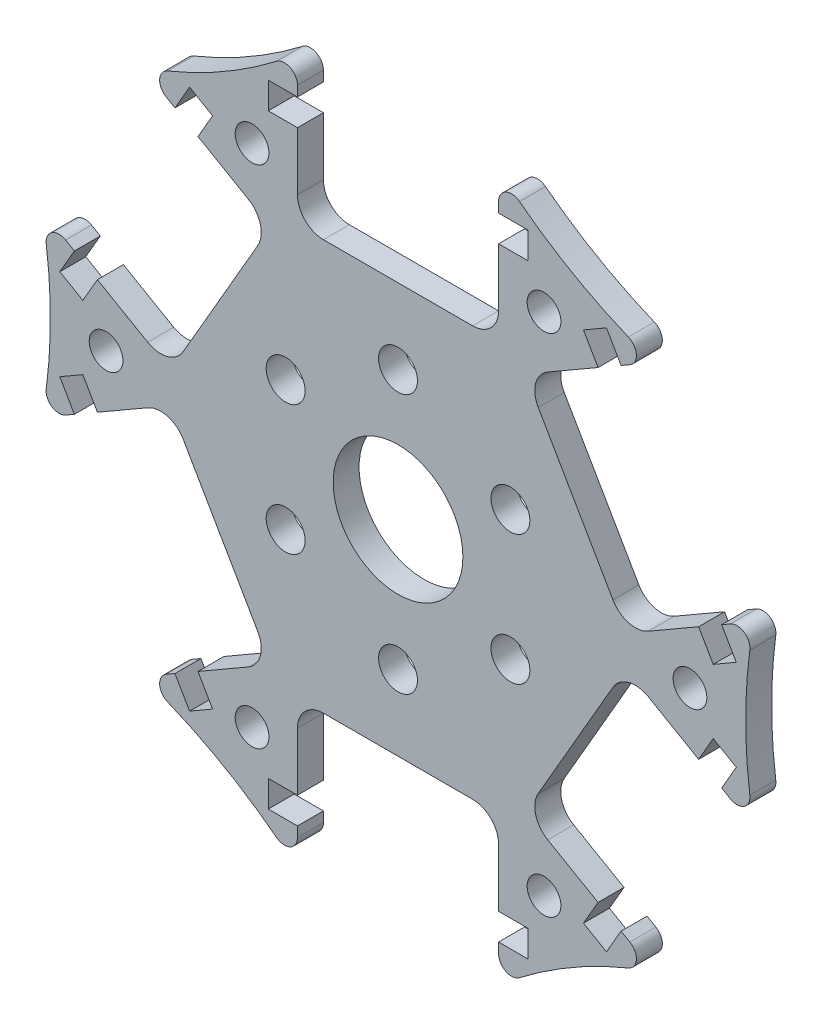
SolidWorks part; units mm, degrees
material "6061 合金"
ref_plane "Front" through (0, 0, 0) normal (0, 0, 1) x (1, 0, 0)
ref_plane "Top" through (0, 0, 0) normal (0, 1, 0) x (1, 0, 0)
ref_plane "Right" through (0, 0, 0) normal (1, 0, 0) x (0, 0, -1)
sketch "ｽｹｯﾁ1" plane through (0, 0, 0) normal (0, 0, 1) x (1, 0, 0)
  circle A0 centre (0, 0) radius 28.3
  dimension "D1" = 56.6
extrude "ﾎﾞｽ - 押し出し1" add sketch "ｽｹｯﾁ1" along normal blind 2
sketch "ｽｹｯﾁ2" plane through (0, 0, 2) normal (0, 0, 1) x (1, 0, 0)
  line L0 (0, 0) -> (0, 50000) construction
  line L1 (7.75, 24.325) -> (10, 24.325)
  line L2 (10, 24.325) -> (10, 22.275)
  line L3 (-7.75, 15.8) -> (-7.75, 22.275)
  line L4 (10, 22.275) -> (7.75, 22.275)
  line L5 (7.75, 27.2181) -> (7.75, 24.325)
  line L6 (7.75, 22.275) -> (7.75, 15.8)
  line L7 (7.75, 15.8) -> (-7.75, 15.8)
  line L8 (-7.75, 22.275) -> (-10, 22.275)
  line L9 (-10, 22.275) -> (-10, 24.325)
  line L10 (-10, 24.325) -> (-7.75, 24.325)
  line L11 (-7.75, 24.325) -> (-7.75, 27.2181)
  line L12 (0, 28.3) -> (16.8233, 28.3) construction
  line L13 (10, 23.3) -> (-10, 23.3) construction
  line L14 (0, 0) -> (28.3, 0) construction
  line L15 (24.9411, 5.4508) -> (26.0661, 3.5022)
  line L16 (26.0661, 3.5022) -> (24.2907, 2.4772)
  line L17 (9.8082, 14.6117) -> (15.4157, 17.8492)
  line L18 (24.2907, 2.4772) -> (23.1657, 4.4258)
  line L19 (27.4466, 6.8974) -> (24.9411, 5.4508)
  line L20 (23.1657, 4.4258) -> (17.5582, 1.1883)
  line L21 (17.5582, 1.1883) -> (9.8082, 14.6117)
  line L22 (15.4157, 17.8492) -> (14.2907, 19.7978)
  line L23 (14.2907, 19.7978) -> (16.0661, 20.8228)
  line L24 (16.0661, 20.8228) -> (17.1911, 18.8742)
  line L25 (17.1911, 18.8742) -> (19.6966, 20.3208)
  line L26 (25.1784, 2.9897) -> (15.1784, 20.3103) construction
  line L27 (17.1911, -18.8742) -> (16.0661, -20.8228)
  line L28 (16.0661, -20.8228) -> (14.2907, -19.7978)
  line L29 (17.5582, -1.1883) -> (23.1657, -4.4258)
  line L30 (14.2907, -19.7978) -> (15.4157, -17.8492)
  line L31 (19.6966, -20.3208) -> (17.1911, -18.8742)
  line L32 (15.4157, -17.8492) -> (9.8082, -14.6117)
  line L33 (9.8082, -14.6117) -> (17.5582, -1.1883)
  line L34 (23.1657, -4.4258) -> (24.2907, -2.4772)
  line L35 (24.2907, -2.4772) -> (26.0661, -3.5022)
  line L36 (26.0661, -3.5022) -> (24.9411, -5.4508)
  line L37 (24.9411, -5.4508) -> (27.4466, -6.8974)
  line L38 (15.1784, -20.3103) -> (25.1784, -2.9897) construction
  line L39 (-7.75, -24.325) -> (-10, -24.325)
  line L40 (-10, -24.325) -> (-10, -22.275)
  line L41 (7.75, -15.8) -> (7.75, -22.275)
  line L42 (-10, -22.275) -> (-7.75, -22.275)
  line L43 (-7.75, -27.2181) -> (-7.75, -24.325)
  line L44 (-7.75, -22.275) -> (-7.75, -15.8)
  line L45 (-7.75, -15.8) -> (7.75, -15.8)
  line L46 (7.75, -22.275) -> (10, -22.275)
  line L47 (10, -22.275) -> (10, -24.325)
  line L48 (10, -24.325) -> (7.75, -24.325)
  line L49 (7.75, -24.325) -> (7.75, -27.2181)
  line L50 (-10, -23.3) -> (10, -23.3) construction
  line L51 (-24.9411, -5.4508) -> (-26.0661, -3.5022)
  line L52 (-26.0661, -3.5022) -> (-24.2907, -2.4772)
  line L53 (-9.8082, -14.6117) -> (-15.4157, -17.8492)
  line L54 (-24.2907, -2.4772) -> (-23.1657, -4.4258)
  line L55 (-27.4466, -6.8974) -> (-24.9411, -5.4508)
  line L56 (-23.1657, -4.4258) -> (-17.5582, -1.1883)
  line L57 (-17.5582, -1.1883) -> (-9.8082, -14.6117)
  line L58 (-15.4157, -17.8492) -> (-14.2907, -19.7978)
  line L59 (-14.2907, -19.7978) -> (-16.0661, -20.8228)
  line L60 (-16.0661, -20.8228) -> (-17.1911, -18.8742)
  line L61 (-17.1911, -18.8742) -> (-19.6966, -20.3208)
  line L62 (-25.1784, -2.9897) -> (-15.1784, -20.3103) construction
  line L63 (-17.1911, 18.8742) -> (-16.0661, 20.8228)
  line L64 (-16.0661, 20.8228) -> (-14.2907, 19.7978)
  line L65 (-17.5582, 1.1883) -> (-23.1657, 4.4258)
  line L66 (-14.2907, 19.7978) -> (-15.4157, 17.8492)
  line L67 (-19.6966, 20.3208) -> (-17.1911, 18.8742)
  line L68 (-15.4157, 17.8492) -> (-9.8082, 14.6117)
  line L69 (-9.8082, 14.6117) -> (-17.5582, 1.1883)
  line L70 (-23.1657, 4.4258) -> (-24.2907, 2.4772)
  line L71 (-24.2907, 2.4772) -> (-26.0661, 3.5022)
  line L72 (-26.0661, 3.5022) -> (-24.9411, 5.4508)
  line L73 (-24.9411, 5.4508) -> (-27.4466, 6.8974)
  line L74 (-15.1784, 20.3103) -> (-25.1784, 2.9897) construction
  line L75 (0, 0) -> (8.6603, 5) construction
  line L76 (0, 0) -> (14.15, 24.5085) construction
  arc A0 (7.75, 27.2181) -> (-7.75, 27.2181) centre (0, 0) ccw
  circle A1 centre (0, 0) radius 28.3 construction
  circle A2 centre (0, 0) radius 5
  circle A3 centre (0, 0) radius 10 construction
  arc A4 (27.4466, 6.8974) -> (19.6966, 20.3208) centre (0, 0) ccw
  arc A5 (19.6966, -20.3208) -> (27.4466, -6.8974) centre (0, 0) ccw
  arc A6 (-7.75, -27.2181) -> (7.75, -27.2181) centre (0, 0) ccw
  arc A7 (-27.4466, -6.8974) -> (-19.6966, -20.3208) centre (0, 0) ccw
  arc A8 (-19.6966, 20.3208) -> (-27.4466, 6.8974) centre (0, 0) ccw
  circle A9 centre (8.6603, 5) radius 1.5
  circle A10 centre (8.6603, -5) radius 1.5
  circle A11 centre (0, -10) radius 1.5
  circle A12 centre (-8.6603, -5) radius 1.5
  circle A13 centre (-8.6603, 5) radius 1.5
  circle A14 centre (0, 10) radius 1.5
  circle A15 centre (0, 0) radius 22.5 construction
  circle A16 centre (11.25, 19.4856) radius 1.3
  circle A17 centre (22.5, 0) radius 1.3
  circle A18 centre (11.25, -19.4856) radius 1.3
  circle A19 centre (-11.25, -19.4856) radius 1.3
  circle A20 centre (-22.5, 0) radius 1.3
  circle A21 centre (-11.25, 19.4856) radius 1.3
  point P99 (0, 0)
  point P111 (0, 0)
  dimension "D1" = 15.5
  dimension "D6" = 10
  dimension "D7" = 20
  dimension "D9" = 30
  dimension "D10" = 3
  dimension "D13" = 45
  dimension "D14" = 2.6
  dimension "D2" = 20
  dimension "D3" = 2.05
  dimension "D4" = 12.5
  dimension "D5" = 5
  dimension "D12" = 60
  dimension "D8" = 6
  dimension "D11" = 6
extrude "ｶｯﾄ - 押し出し1" cut sketch "ｽｹｯﾁ2" against normal through all
sketch "ｽｹｯﾁ3" plane through (0, 0, 2) normal (0, 0, 1) x (1, 0, 0)
  line L0 (0, 0) -> (14.15, 24.5085) construction
  arc A0 (19.6966, 20.3208) -> (7.75, 27.2181) centre (0, 0) ccw construction
  arc A1 (7.75, 27.2181) -> (19.6966, 20.3208) centre (31.65, 54.8194) ccw
  arc A2 (19.6966, 20.3208) -> (7.75, 27.2181) centre (0, 0) ccw
  arc A3 (27.4466, 6.8974) -> (27.4466, -6.8974) centre (63.3, 0) ccw
  arc A4 (27.4466, -6.8974) -> (27.4466, 6.8974) centre (0, 0) ccw
  arc A5 (19.6966, -20.3208) -> (7.75, -27.2181) centre (31.65, -54.8194) ccw
  arc A6 (7.75, -27.2181) -> (19.6966, -20.3208) centre (0, 0) ccw
  arc A7 (-7.75, -27.2181) -> (-19.6966, -20.3208) centre (-31.65, -54.8194) ccw
  arc A8 (-19.6966, -20.3208) -> (-7.75, -27.2181) centre (0, 0) ccw
  arc A9 (-27.4466, -6.8974) -> (-27.4466, 6.8974) centre (-63.3, 0) ccw
  arc A10 (-27.4466, 6.8974) -> (-27.4466, -6.8974) centre (0, 0) ccw
  arc A11 (-19.6966, 20.3208) -> (-7.75, 27.2181) centre (-31.65, 54.8194) ccw
  arc A12 (-7.75, 27.2181) -> (-19.6966, 20.3208) centre (0, 0) ccw
  point P27 (0, 0)
  dimension "D1" = 35
  dimension "D2" = 6
extrude "ｶｯﾄ - 押し出し3" cut sketch "ｽｹｯﾁ3" against normal through all
fillet "ﾌｨﾚｯﾄ2" radius 2 12 edges at (-9.8082, 14.6117, 1) (-17.5582, -1.1883, 1) (-17.5582, 1.1883, 1) (-7.75, -15.8, 1) (-9.8082, -14.6117, 1) (9.8082, -14.6117, 1) (7.75, -15.8, 1) (17.5582, -1.1883, 1) (17.5582, 1.1883, 1) (9.8082, 14.6117, 1) (7.75, 15.8, 1) (-7.75, 15.8, 1)
fillet "ﾌｨﾚｯﾄ1" radius 1 12 edges at (19.6966, 20.3208, 1) (7.75, 27.2181, 1) (-19.6966, 20.3208, 1) (-7.75, 27.2181, 1) (-27.4466, 6.8974, 1) (-27.4466, -6.8974, 1) (-19.6966, -20.3208, 1) (-7.75, -27.2181, 1) (7.75, -27.2181, 1) (19.6966, -20.3208, 1) (27.4466, -6.8974, 1) (27.4466, 6.8974, 1)
